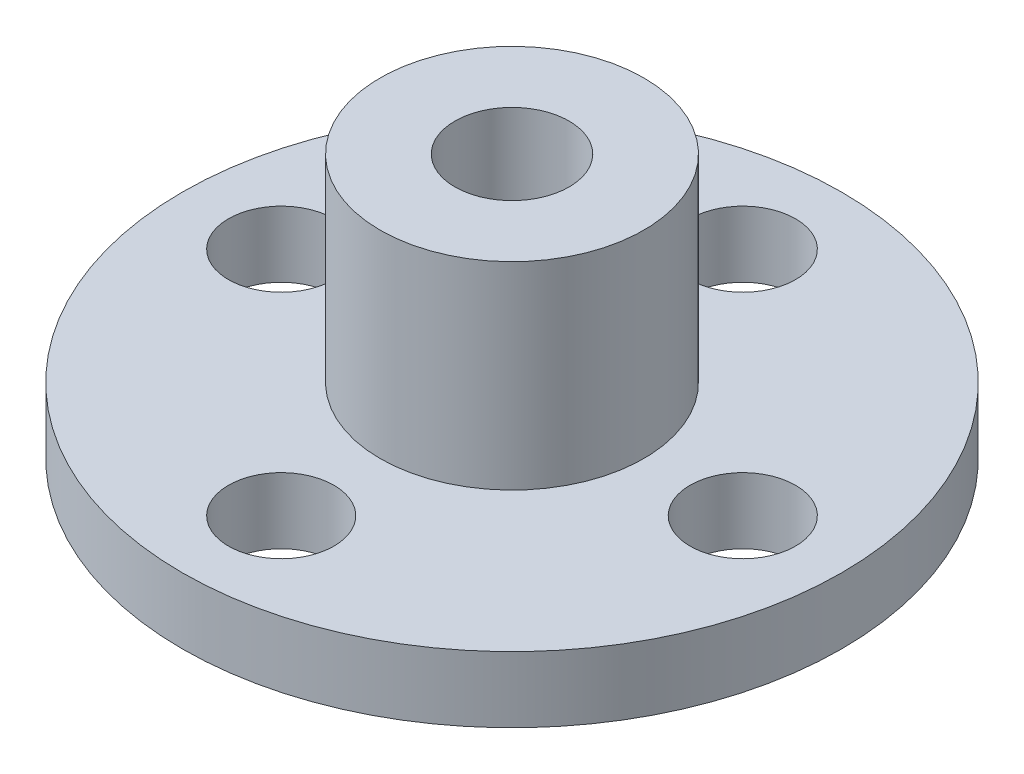
SolidWorks part; units mm, degrees
ref_plane "Front Plane" through (0, 0, 0) normal (0, 0, 1) x (1, 0, 0)
ref_plane "Top Plane" through (0, 0, 0) normal (0, 1, 0) x (1, 0, 0)
ref_plane "Right Plane" through (0, 0, 0) normal (1, 0, 0) x (0, 0, -1)
sketch "Sketch1" plane through (0, 0, 0) normal (0, 1, 0) x (1, 0, 0)
  circle A0 centre (0, 0) radius 2.75
  circle A1 centre (0, 0) radius 6.35
  dimension "D1" = 5.5
  dimension "D2" = 12.7
extrude "Boss-Extrude1" add sketch "Sketch1" along normal blind 12.7
sketch "Sketch2" plane through (0, 0, 0) normal (0, -1, 0) x (1, 0, 0)
  line L0 (0, 0) -> (0, 11.1125) construction
  line L1 (0, 6.35) -> (0, 15.875) construction
  line L2 (11.1125, 0) -> (0, 0) construction
  circle A0 centre (0, 0) radius 15.875
  circle A1 centre (0, 11.1125) radius 2.54
  circle A2 centre (0, 0) radius 6.35 construction
  circle A3 centre (0, 0) radius 6.35
  circle A4 centre (11.1125, 0) radius 2.54
  circle A5 centre (0, -11.1125) radius 2.54
  circle A6 centre (-11.1125, 0) radius 2.54
  point P19 (0, 0)
  dimension "D1" = 31.75
  dimension "D2" = 5.08
  dimension "D3" = 4
extrude "Boss-Extrude2" add sketch "Sketch2" against normal blind 3.175
